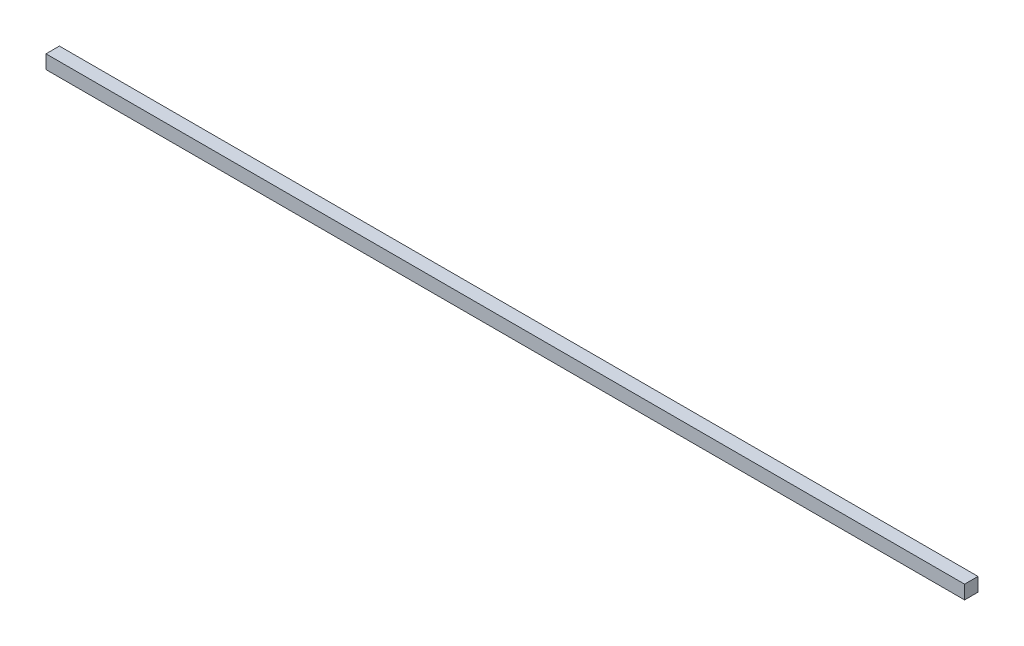
SolidWorks part; units mm, degrees
ref_plane "前视基准面" through (0, 0, 0) normal (0, 0, 1) x (1, 0, 0)
ref_plane "上视基准面" through (0, 0, 0) normal (0, 1, 0) x (1, 0, 0)
ref_plane "右视基准面" through (0, 0, 0) normal (1, 0, 0) x (0, 0, -1)
sketch "Model" plane through (0, 0, 0) normal (0, 0, 1) x (1, 0, 0)
  line L0 (921.8701, 62.105) -> (579.5034, 62.105)
  line L1 (921.8701, 57.005) -> (579.5034, 57.005)
  line L2 (579.5034, 57.005) -> (579.5034, 62.105)
  line L3 (921.8701, 62.105) -> (921.8701, 57.005)
extrude "凸台-拉伸1" add sketch "Model" along normal blind 5
